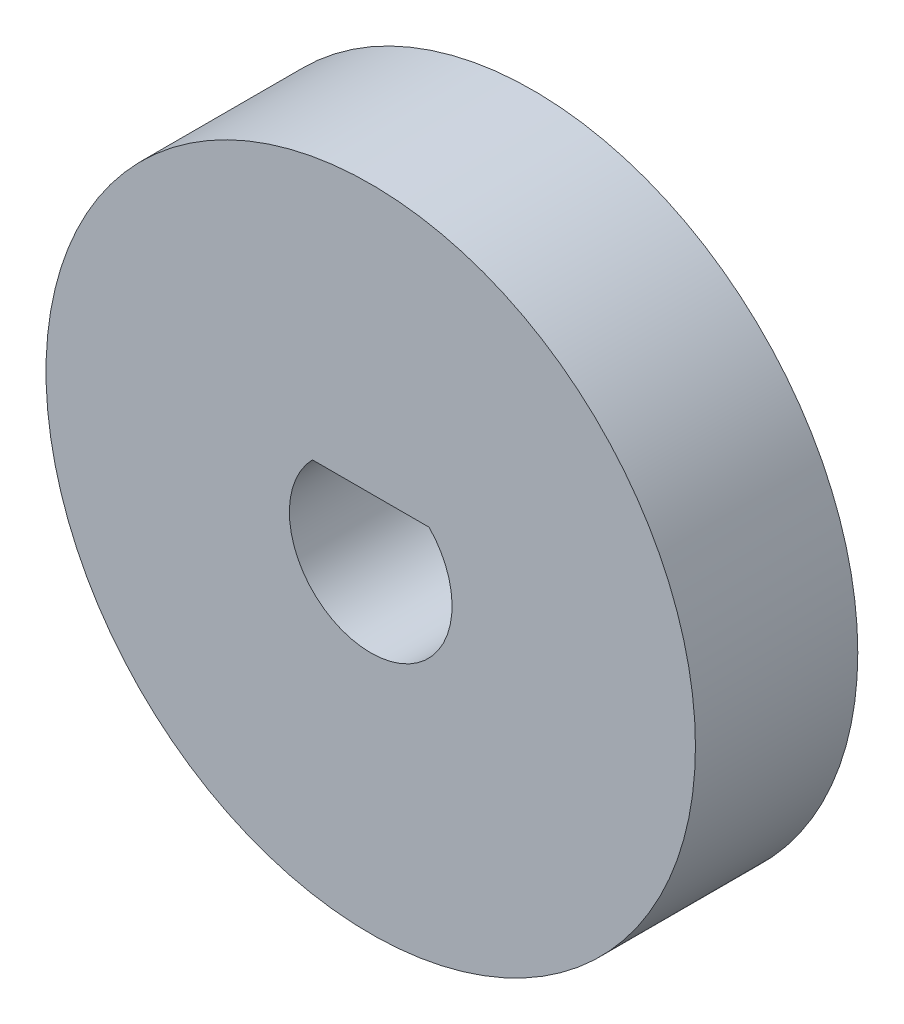
SolidWorks part; units mm, degrees
ref_plane "Front Plane" through (0, 0, 0) normal (0, 0, 1) x (1, 0, 0)
ref_plane "Top Plane" through (0, 0, 0) normal (0, 1, 0) x (1, 0, 0)
ref_plane "Right Plane" through (0, 0, 0) normal (1, 0, 0) x (0, 0, -1)
sketch "Sketch1" plane through (0, 0, 0) normal (0, 0, 1) x (1, 0, 0)
  line L0 (-2.2825, 2.2161) -> (2.2825, 2.2161)
  arc A1 (-2.2825, 2.2161) -> (2.2825, 2.2161) centre (0, 0) ccw
  circle A2 centre (0, 0) radius 12.7
  dimension "D1" = 6.3627
  dimension "D3" = 25.4
  dimension "D2" = 2.2161
extrude "Boss-Extrude1" add sketch "Sketch1" along normal blind 6.35
